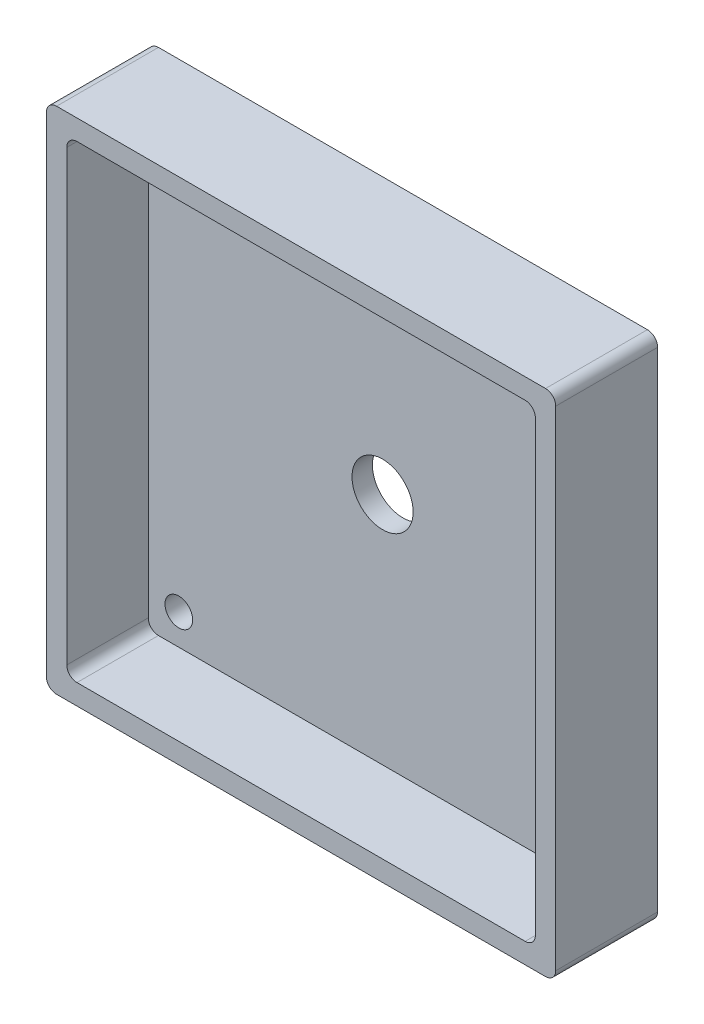
SolidWorks part; units mm, degrees
ref_plane "Front Plane" through (0, 0, 0) normal (0, 0, 1) x (1, 0, 0)
ref_plane "Top Plane" through (0, 0, 0) normal (0, 1, 0) x (1, 0, 0)
ref_plane "Right Plane" through (0, 0, 0) normal (1, 0, 0) x (0, 0, -1)
sketch "Sketch1" plane through (0, 0, 0) normal (0, 0, 1) x (1, 0, 0)
  line L1 (50, 50) -> (-50, 50)
  line L2 (50, 50) -> (50, -50)
  line L3 (50, -50) -> (-50, -50)
  line L4 (-50, 50) -> (-50, -50)
  line L5 (50, 50) -> (-50, -50) construction
  line L6 (50, -50) -> (-50, 50) construction
  point P0 (0, 0)
  dimension "D1" = 100
  dimension "D2" = 100
extrude "Boss-Extrude1" add sketch "Sketch1" along normal blind 20
ref_plane "Plane1" through (0, 0, 20) normal (0, 0, 1) x (1, 0, 0)
sketch "Sketch2" plane through (0, 0, 20) normal (0, 0, 1) x (1, 0, 0)
  line L1 (46, -46) -> (-46, -46)
  line L2 (46, -46) -> (46, 46)
  line L3 (46, 46) -> (-46, 46)
  line L4 (-46, -46) -> (-46, 46)
  line L5 (46, -46) -> (-46, 46) construction
  line L6 (46, 46) -> (-46, -46) construction
  point P0 (0, 0)
  dimension "D1" = 92
  dimension "D2" = 92
extrude "Cut-Extrude1" cut sketch "Sketch2" against normal blind 16
fillet "Fillet1" radius 2 8 edges at (-46, 46, 12) (46, 46, 12) (46, -46, 12) (-46, -46, 12) (50, -50, 10) (-50, -50, 10) (-50, 50, 10) (50, 50, 10)
sketch "Sketch3" plane through (0, 0, 0) normal (0, 0, 1) x (1, 0, 0)
  circle A0 centre (0, 0) radius 6
  circle A1 centre (-40, 40) radius 2.714
  circle A2 centre (40, 40) radius 2.714
  circle A3 centre (40, -40) radius 2.714
  circle A4 centre (-40, -40) radius 2.714
  point P14 (0, 0)
  dimension "D1" = 12
  dimension "D2" = 40
  dimension "D3" = 40
  dimension "D4" = 4
extrude "Cut-Extrude2" cut sketch "Sketch3" along normal blind 16
